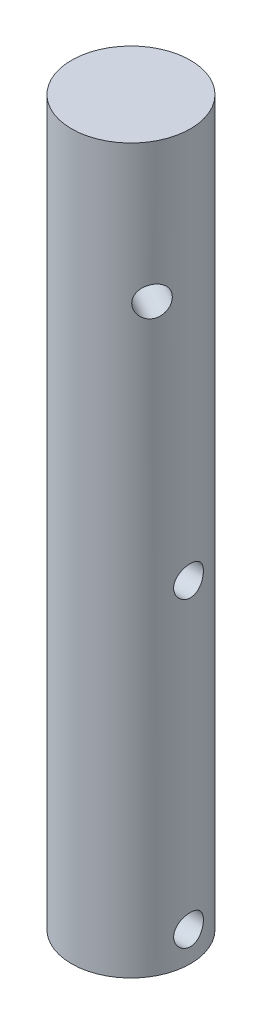
SolidWorks part; units mm, degrees
other "Driven Wheel Axle"
other "Driven Wheel Axle Left"
ref_plane "Front Plane" through (0, 0, 0) normal (0, 0, 1) x (1, 0, 0)
ref_plane "Top Plane" through (0, 0, 0) normal (0, 1, 0) x (1, 0, 0)
ref_plane "Right Plane" through (0, 0, 0) normal (1, 0, 0) x (0, 0, -1)
sketch3d "Twelve millimetre axle stock sketch datum points"
  point P0 (-19.0092, -283, -53.2449)
  point P1 (-9.0092, -283, -53.2449)
  point P2 (-19.0092, -283, -63.2449)
ref_plane "Twelve millimetre axle stock sketch plane" through (0, -283, 0) normal (0, 1, 0) x (1, 0, 0)
sketch "Twelve millimetre axle stock sketch" plane through (0, -283, 0) normal (0, 1, 0) x (1, 0, 0)
  circle A0 centre (-19.0092, 53.2449) radius 6
extrude "Twelve millimetre axle stock" add sketch "Twelve millimetre axle stock sketch" along normal blind 73 separate body
sketch3d "Motor coupling socket sketch datum points"
  point P0 (-19.0092, -232, -53.2449)
  point P1 (-9.0092, -232, -53.2449)
  point P2 (-19.0092, -232, -63.2449)
ref_plane "Motor coupling socket sketch plane" through (0, -232, 0) normal (0, 1, 0) x (1, 0, 0)
sketch "Motor coupling socket sketch" plane through (0, -232, 0) normal (0, 1, 0) x (1, 0, 0)
  circle A0 centre (-19.0092, 53.2449) radius 3.05
extrude "Motor coupling socket" cut sketch "Motor coupling socket sketch" along normal blind 22.1
sketch3d "Front collar pin sketch datum points"
  point P0 (-26.0092, -213, -53.2449)
  point P1 (-26.0092, -203, -53.2449)
  point P2 (-26.0092, -213, -43.2449)
ref_plane "Front collar pin sketch plane" through (-26.0092, 0, 0) normal (1, 0, 0) x (0, 0, -1)
sketch "Front collar pin sketch" plane through (-26.0092, 0, 0) normal (1, 0, 0) x (0, 0, -1)
  circle A0 centre (53.2449, -213) radius 1.5
extrude "Front collar pin" cut sketch "Front collar pin sketch" along normal blind 14
sketch3d "Rear collar pin sketch datum points"
  point P0 (-26.0092, -243.5, -53.2449)
  point P1 (-26.0092, -233.5, -53.2449)
  point P2 (-26.0092, -243.5, -43.2449)
ref_plane "Rear collar pin sketch plane" through (-26.0092, 0, 0) normal (1, 0, 0) x (0, 0, -1)
sketch "Rear collar pin sketch" plane through (-26.0092, 0, 0) normal (1, 0, 0) x (0, 0, -1)
  circle A0 centre (53.2449, -243.5) radius 1.5
extrude "Rear collar pin" cut sketch "Rear collar pin sketch" along normal blind 14
sketch3d "Hub drive pin sketch datum points"
  point P0 (-25.0714, -269, -56.7449)
  point P1 (-20.0714, -269, -65.4051)
  point P2 (-25.0714, -259, -56.7449)
ref_plane "Hub drive pin sketch plane" through (-43.3748, 0, -25.0424) normal (0.866, 0, 0.5) x (0.5, 0, -0.866)
sketch "Hub drive pin sketch" plane through (-43.3748, 0, -25.0424) normal (0.866, 0, 0.5) x (0.5, 0, -0.866)
  circle A0 centre (36.6068, -269) radius 1.5
extrude "Hub drive pin" cut sketch "Hub drive pin sketch" along normal blind 14
sketch3d "Mirror1 profile datum points"
  point P0 (0, 0, 0)
  point P1 (10, 0, 0)
  point P2 (0, 0, 10)
ref_plane "Mirror1 profile plane" through (0, 0, 0) normal (0, -1, 0) x (-1, 0, 0)
mirror "Mirror1" about plane through (0, 0, 0) normal (0, -1, 0) of bodies 105
delete or keep bodies "Remove1" type delete bodies bodies 105
